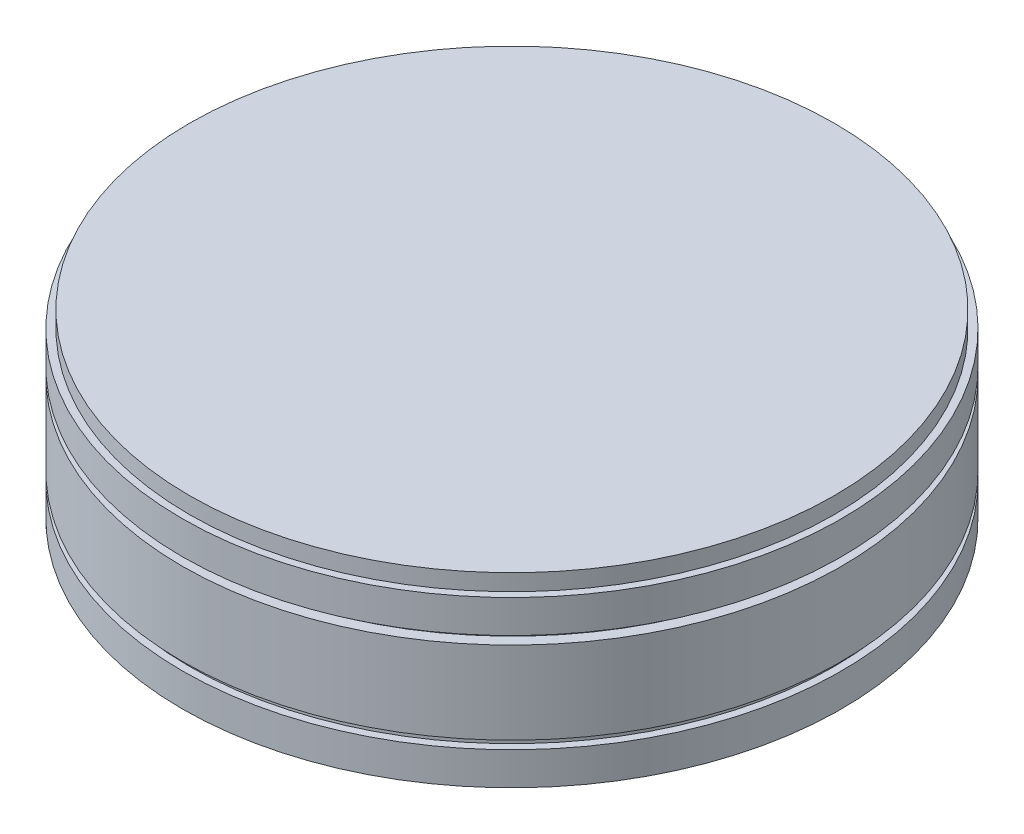
SolidWorks part; units mm, degrees
ref_plane "Спереди" through (0, 0, 0) normal (0, 0, 1) x (1, 0, 0)
ref_plane "Сверху" through (0, 0, 0) normal (0, 1, 0) x (1, 0, 0)
ref_plane "Справа" through (0, 0, 0) normal (1, 0, 0) x (0, 0, -1)
sketch "Sketch1" plane through (0, 0, 0) normal (0, 1, 0) x (1, 0, 0)
  circle A0 centre (0, 0) radius 20
  dimension "D1" = 40
extrude "Boss-Extrude1" add sketch "Sketch1" along normal blind 2
sketch "Sketch2" plane through (0, 2, 0) normal (0, 1, 0) x (1, 0, 0)
  circle A0 centre (0, 0) radius 19.5495
extrude "Boss-Extrude2" add sketch "Sketch2" along normal blind 0.5
sketch "Sketch3" plane through (0, 2.5, 0) normal (0, 1, 0) x (1, 0, 0)
  circle A0 centre (0, 0) radius 20
extrude "Boss-Extrude3" add sketch "Sketch3" along normal blind 5
sketch "Sketch4" plane through (0, 7.5, 0) normal (0, 1, 0) x (1, 0, 0)
  circle A0 centre (0, 0) radius 19.3382
extrude "Boss-Extrude4" add sketch "Sketch4" along normal blind 0.5
sketch "Sketch5" plane through (0, 8, 0) normal (0, 1, 0) x (1, 0, 0)
  circle A0 centre (0, 0) radius 20
extrude "Boss-Extrude5" add sketch "Sketch5" along normal blind 2
sketch "Sketch6" plane through (0, 10, 0) normal (0, 1, 0) x (1, 0, 0)
  circle A0 centre (0, 0) radius 19.5692
extrude "Boss-Extrude6" add sketch "Sketch6" along normal blind 1
